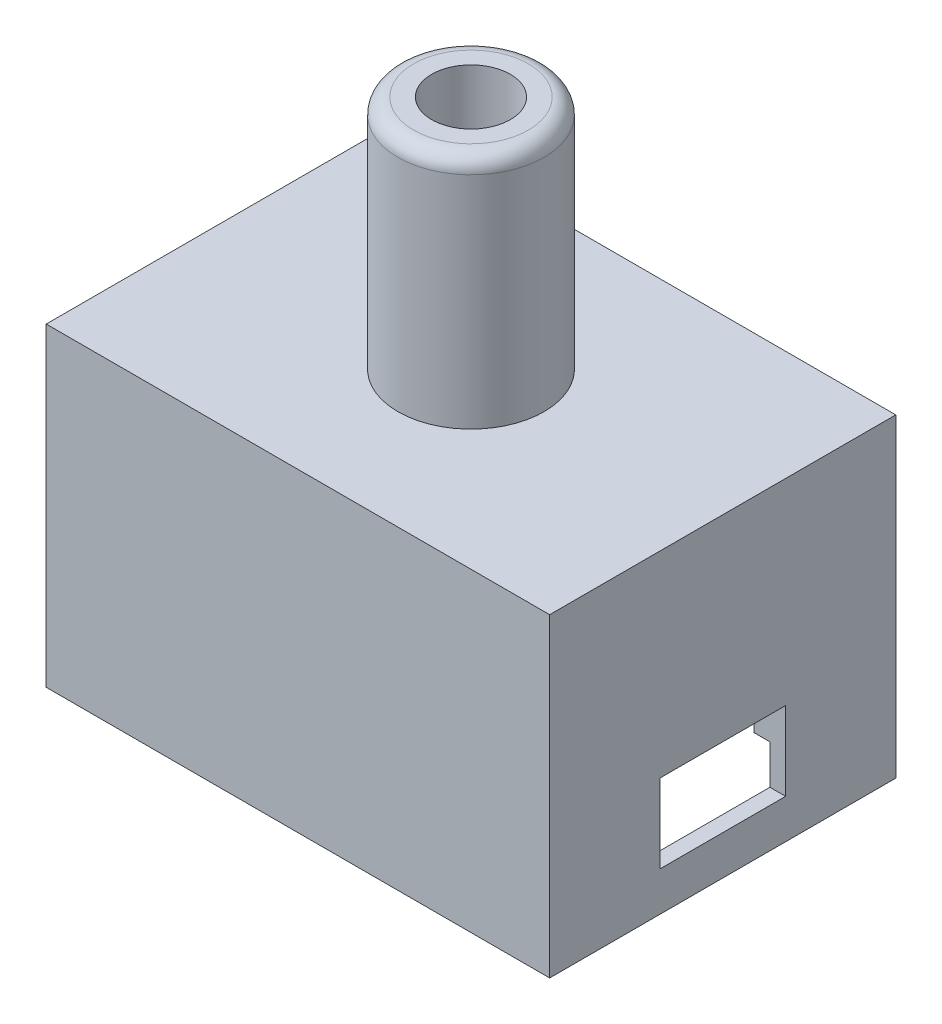
SolidWorks part; units mm, degrees
material "Custom Plastic"
ref_plane "Front Plane" through (0, 0, 0) normal (0, 0, 1) x (1, 0, 0)
ref_plane "Top Plane" through (0, 0, 0) normal (0, 1, 0) x (1, 0, 0)
ref_plane "Right Plane" through (0, 0, 0) normal (1, 0, 0) x (0, 0, -1)
sketch "Sketch1" plane through (0, 0, 0) normal (0, 1, 0) x (1, 0, 0)
  line L1 (-16, -11) -> (16, -11)
  line L2 (-16, -11) -> (-16, 11)
  line L3 (-16, 11) -> (16, 11)
  line L4 (16, -11) -> (16, 11)
  line L5 (-16, -11) -> (16, 11) construction
  line L6 (-16, 11) -> (16, -11) construction
  point P0 (0, 0)
  dimension "D1" = 32
  dimension "D2" = 22
extrude "Boss-Extrude1" add sketch "Sketch1" along normal blind 20
sketch "Sketch2" plane through (0, 20, 0) normal (0, 1, 0) x (1, 0, 0)
  circle A0 centre (0, 0) radius 4.65
  dimension "D1" = 9.3
extrude "Boss-Extrude2" add sketch "Sketch2" along normal blind 15
sketch "Sketch3" plane through (0, 0, 0) normal (0, -1, 0) x (1, 0, 0)
  line L3 (15, -10) -> (-15, -10)
  line L4 (15, -10) -> (15, 10)
  line L5 (15, 10) -> (-15, 10)
  line L6 (-15, -10) -> (-15, 10)
  line L7 (15, -10) -> (-15, 10) construction
  line L8 (15, 10) -> (-15, -10) construction
  point P5 (0, 0)
  dimension "D1" = 20
  dimension "D2" = 30
extrude "Cut-Extrude1" cut sketch "Sketch3" against normal offset from surface (19 mm away) 1 up to face at (0, 20, 4.65)
sketch "Sketch4" plane through (0, 19, 0) normal (0, -1, 0) x (1, 0, 0)
  circle A0 centre (0, 0) radius 2.5
  dimension "D1" = 5
extrude "Cut-Extrude2" cut sketch "Sketch4" against normal through all
fillet "Fillet1" radius 1 1 edges at (0, 35, 4.65)
fillet "Fillet2" radius 1 1 edges at (0, 19, -2.5)
sketch "Sketch5" plane through (0, 19, 0) normal (0, -1, 0) x (1, 0, 0)
  line L5 (14, -9) -> (-14, -9)
  line L6 (14, -9) -> (14, 9)
  line L7 (14, 9) -> (-14, 9)
  line L8 (-14, -9) -> (-14, 9)
  line L9 (14, -9) -> (-14, 9) construction
  line L10 (14, 9) -> (-14, -9) construction
  line L11 (15, -10) -> (-15, -10)
  line L12 (15, -10) -> (15, 10)
  line L13 (15, 10) -> (-15, 10)
  line L14 (-15, -10) -> (-15, 10)
  line L15 (15, -10) -> (-15, 10) construction
  line L16 (15, 10) -> (-15, -10) construction
  point P5 (0, 0)
  point P6 (0, 0)
extrude "Boss-Extrude3" add sketch "Sketch5" along normal blind 14
sketch "Sketch8" plane through (16, 0, 0) normal (1, 0, 0) x (0, 0, -1)
  line L0 (10, 5) -> (-10, 5) construction
  line L1 (4, 2.5) -> (-4, 2.5)
  line L2 (4, 2.5) -> (4, 7.5)
  line L3 (4, 7.5) -> (-4, 7.5)
  line L4 (-4, 2.5) -> (-4, 7.5)
  line L5 (4, 2.5) -> (-4, 7.5) construction
  line L6 (4, 7.5) -> (-4, 2.5) construction
  point P0 (0, 5)
  dimension "D1" = 8
  dimension "D2" = 5
extrude "Cut-Extrude3" cut sketch "Sketch8" against normal up to surface (2 mm away) up to face at (14, 12, 0)
